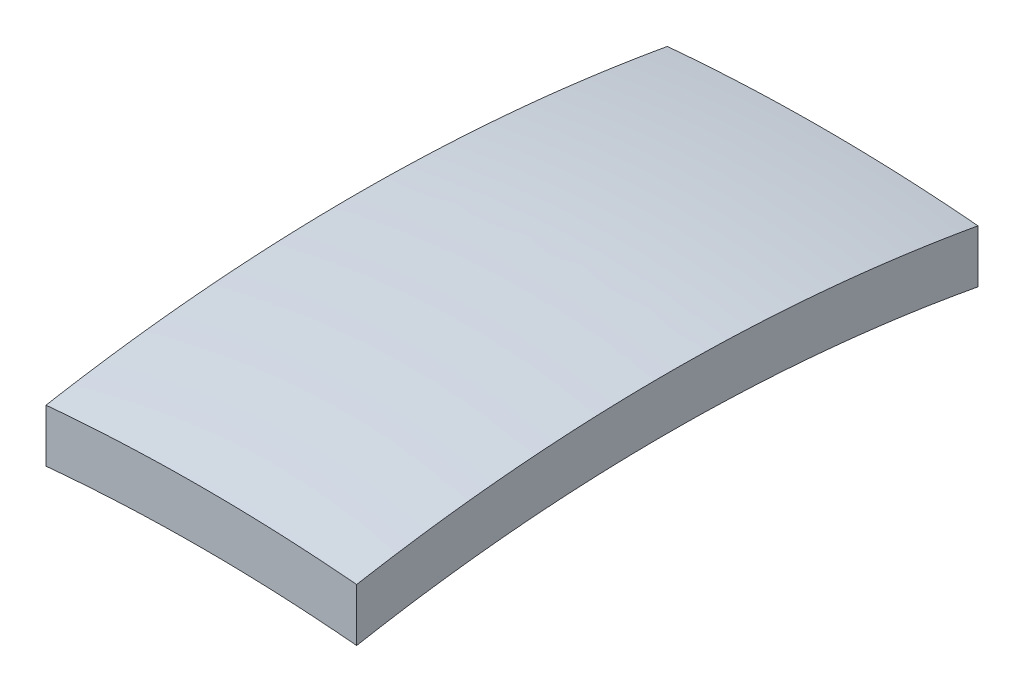
SolidWorks part; units mm, degrees
material "Acrylic (Medium-high impact)"
ref_plane "Front" through (0, 0, 0) normal (0, 0, 1) x (1, 0, 0)
ref_plane "Top" through (0, 0, 0) normal (0, 1, 0) x (1, 0, 0)
ref_plane "Right" through (0, 0, 0) normal (1, 0, 0) x (0, 0, -1)
sketch "Sketch1" plane through (0, 0, 0) normal (1, 0, 0) x (0, 0, -1)
  line L0 (0, 342) -> (0, 332) construction
  line L1 (242.6582, 241) -> (246.5, 241) construction
  line L2 (246.5, 241) -> (246.5, 229) construction
  line L3 (246.5, 229) -> (240.3809, 229) construction
  line L4 (0, 332) -> (0, 0) construction
  line L5 (0, 0) -> (53.5006, 337.7894) construction
  line L6 (26.55, 278) -> (44.0309, 278) construction
  line L7 (26.55, 258) -> (40.8632, 258) construction
  line L8 (26.25, 284) -> (26.25, 235.5) construction
  line L9 (23.25, 232.5) -> (0, 232.5) construction
  line L10 (26.55, 278) -> (26.55, 258) construction
  line L11 (22.2, 232.5) -> (22.2, 210.5) construction
  line L12 (21.2, 209.5) -> (0, 209.5) construction
  line L13 (49.2591, 319) -> (50.7013, 328.1057) construction
  line L14 (49.2591, 319) -> (39.2252, 310.1228) construction
  line L15 (29.1813, 290.9057) -> (36.1857, 297.6697) construction
  line L16 (27, 278) -> (27, 279) construction
  line L17 (27, 279) -> (42, 279) construction
  line L18 (42, 279) -> (42, 278) construction
  line L19 (26.4, 284) -> (43.7156, 284) construction
  line L20 (43.7156, 284) -> (48.9147, 316.8261) construction
  line L21 (48.4509, 317.3504) -> (40.8872, 310.6585) construction
  line L22 (40.5498, 309.9096) -> (40.5498, 304.1375) construction
  line L23 (29.2855, 290.7978) -> (36.2899, 297.5618) construction
  line L24 (36.2899, 297.5618) -> (38.7788, 299.9654) construction
  line L25 (48.4509, 317.3504) -> (48.9147, 316.8261) construction
  line L26 (30, 284) -> (30, 279) construction
  line L27 (40.7818, 311.5) -> (41.2457, 310.9757) construction
  line L28 (40, 284) -> (40, 279) construction
  line L29 (49.2591, 319) -> (49.7229, 318.4757) construction
  line L30 (49.7229, 318.4757) -> (48.4509, 317.3504) construction
  arc A0 (0, 342) -> (242.6582, 241) centre (0, 0) cw construction
  arc A1 (0, 332) -> (240.3809, 229) centre (0, 0) cw construction
  arc A2 (0, 330) -> (36.419, 314.7024) centre (0, 279) cw construction
  arc A3 (26.25, 284) -> (29.1813, 290.9057) centre (35.85, 284) cw construction
  arc A4 (23.25, 232.5) -> (26.25, 235.5) centre (23.25, 235.5) ccw construction
  arc A5 (36.1857, 297.6697) -> (36.419, 314.7024) centre (27.8498, 306.3018) ccw construction
  arc A6 (21.2, 209.5) -> (22.2, 210.5) centre (21.2, 210.5) ccw construction
  arc A7 (26.4, 284) -> (29.2855, 290.7978) centre (35.85, 284) cw construction
  arc A8 (40.5498, 309.9096) -> (40.8872, 310.6585) centre (41.5498, 309.9096) cw construction
  arc A9 (36.2899, 297.5618) -> (36.5261, 314.8074) centre (27.8498, 306.3018) ccw construction
  arc A10 (38.7788, 299.9654) -> (40.5498, 304.1375) centre (34.7498, 304.1375) ccw construction
  point P21 (0, 279)
  point P34 (22.2, 209.5)
  dimension "D1" = 342
  dimension "D2" = 332
  dimension "D16" = 51
  dimension "D17" = 9.6
  dimension "D19" = 140.5
  dimension "D20" = 12
  dimension "D21" = 51.5
  dimension "D23" = 3
  dimension "D24" = 1
  dimension "D31" = 1
  dimension "D32" = 5.8
  dimension "D3" = 241
  dimension "D4" = 229
  dimension "D5" = 246.5
  dimension "D6" = 9
  dimension "D7" = 278
  dimension "D8" = 20
  dimension "D9" = 26.25
  dimension "D10" = 0.3
  dimension "D11" = 232.5
  dimension "D12" = 23
  dimension "D13" = 22.2
  dimension "D14" = 1.25
  dimension "D15" = 97.5
  dimension "D18" = 44
  dimension "D22" = 13
  dimension "D25" = 15
  dimension "D26" = 1
  dimension "D27" = 27
  dimension "D28" = 0.7
  dimension "D29" = 0.7
  dimension "D33" = 30
  dimension "D34" = 5
  dimension "D35" = 10
  dimension "D36" = 0.7
  dimension "D37" = 7.5
  dimension "D30" = 0.15
sketch "Sketch2" plane through (0, 0, 0) normal (1, 0, 0) x (0, 0, -1)
  line L0 (246.5, 236.9583) -> (242.5, 236.9583) construction
  line L1 (242.5, 236.9583) -> (242.5, 241.1592)
  line L2 (246.5, 236.9583) -> (246.5, 230.9583) construction
  line L3 (0, 342) -> (0, 332) construction
  line L4 (244.5, 228.547) -> (-244.5, 228.547) construction
  line L5 (246.5, 237.0691) -> (246.5, 236.9583) construction
  line L6 (246.5, 241) -> (246.5, 229) construction
  line L7 (0, 342) -> (0, 332)
  line L8 (244.5, 228.547) -> (244.5, 230.96) construction
  line L9 (244.5, 229.7535) -> (240.1118, 229.7535) construction
  line L10 (242.5, 236.9583) -> (232.5398, 236.9583) construction
  line L11 (242.5, 241.1592) -> (238.5, 241.1592)
  line L12 (246.5, 230.9583) -> (238.5, 230.9583) construction
  line L13 (238.5, 241.1592) -> (238.5, 245.1158)
  line L14 (242.5, 236.9583) -> (242.5, 234.9561)
  line L15 (242.5, 234.9561) -> (234.5626, 234.9561)
  arc A1 (240.3809, 229) -> (0, 332) centre (0, 0) ccw construction
  arc A2 (246.5, 237.0691) -> (238.5, 245.1158) centre (0, 0) ccw construction
  arc A3 (238.5, 245.1158) -> (0, 342) centre (0, 0) ccw
  arc A4 (234.5626, 234.9561) -> (0, 332) centre (0, 0) ccw
  dimension "D1" = 4
  dimension "D2" = 8
  dimension "D3" = 6
  dimension "D4" = 2.4113
  dimension "D5" = 4.3882
  dimension "D6" = 4
  dimension "D7" = 2.0022
revolve "Revolve1" add sketch "Sketch2" angle 360 about L7
sketch "Sketch3" plane through (0, 234.9561, 0) normal (0, -1, 0) x (1, 0, 0)
  line L1 (-30, -60) -> (30, -60)
  line L2 (-30, -60) -> (-30, 60)
  line L3 (-30, 60) -> (30, 60)
  line L4 (30, -60) -> (30, 60)
  line L5 (-30, -60) -> (30, 60) construction
  line L6 (-30, 60) -> (30, -60) construction
  circle A0 centre (0, 0) radius 281.9269
  point P0 (0, 0)
  dimension "D1" = 60
  dimension "D2" = 120
extrude "Cut-Extrude1" cut sketch "Sketch3" against normal up to next
